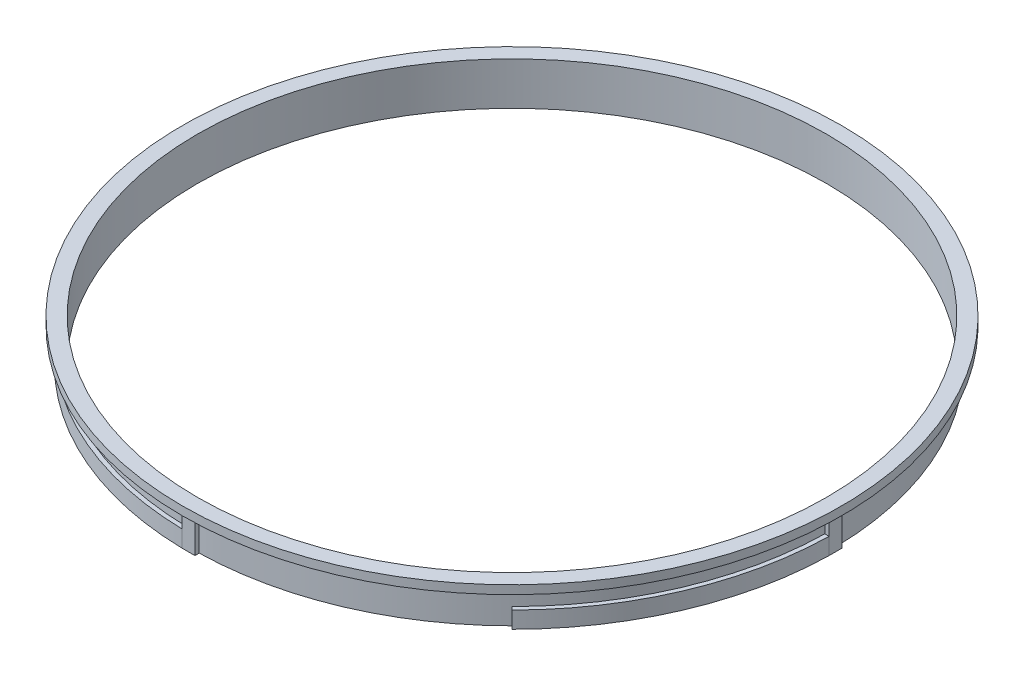
SolidWorks part; units mm, degrees
ref_plane "前视基准面" through (0, 0, 0) normal (0, 0, 1) x (1, 0, 0)
ref_plane "上视基准面" through (0, 0, 0) normal (0, 1, 0) x (1, 0, 0)
ref_plane "右视基准面" through (0, 0, 0) normal (1, 0, 0) x (0, 0, -1)
sketch "草图1" plane through (0, 0, 0) normal (0, 1, 0) x (1, 0, 0)
  circle A0 centre (0, 0) radius 73.5
  circle A1 centre (0, 0) radius 74.6
  dimension "D1" = 147
  dimension "D2" = 149.2
extrude "凸台-拉伸1" add sketch "草图1" along normal blind 10
sketch "草图2" plane through (0, 0, 0) normal (0, 1, 0) x (1, 0, 0)
  line L0 (0, 0) -> (74.6, 0) construction
  line L2 (75.5849, -1.5) -> (74.5849, -1.5)
  line L3 (75.5849, -1.5) -> (75.5849, 1.5)
  line L4 (75.5849, 1.5) -> (74.5849, 1.5)
  line L5 (74.5849, -1.5) -> (74.5849, 1.5)
  line L6 (75.5849, -1.5) -> (74.5849, 1.5) construction
  line L7 (75.5849, 1.5) -> (74.5849, -1.5) construction
  line L31 (-1.5, -75.5849) -> (-1.5, -74.5849)
  line L32 (-1.5, -75.5849) -> (1.5, -75.5849)
  line L33 (-1.5, -74.5849) -> (1.5, -74.5849)
  line L34 (1.5, -75.5849) -> (1.5, -74.5849)
  line L35 (-75.5849, 1.5) -> (-74.5849, 1.5)
  line L36 (-75.5849, 1.5) -> (-75.5849, -1.5)
  line L37 (-74.5849, 1.5) -> (-74.5849, -1.5)
  line L38 (-75.5849, -1.5) -> (-74.5849, -1.5)
  line L39 (1.5, 75.5849) -> (1.5, 74.5849)
  line L40 (1.5, 75.5849) -> (-1.5, 75.5849)
  line L41 (1.5, 74.5849) -> (-1.5, 74.5849)
  line L42 (-1.5, 75.5849) -> (-1.5, 74.5849)
  circle A0 centre (0, 0) radius 74.6 construction
  point P6 (75.0849, 0)
  point P11 (0, 0)
  point P24 (0, 0)
  point P27 (0, 0)
  dimension "D1" = 1
  dimension "D2" = 3
  dimension "D3" = 4
extrude "凸台-拉伸2" add sketch "草图2" along normal up to surface (10 mm away) up to face at (0, 10, 74.6)
sketch "草图3" plane through (0, 0, 0) normal (0, 1, 0) x (1, 0, 0)
  line L0 (0, 75.835) -> (0, 0) construction
  line L2 (0, 0) -> (53.4571, 53.4571) construction
  line L11 (1.5, 75.5849) -> (1.5, 74.5849)
  line L13 (53.4571, 53.4571) -> (52.7502, 52.7502)
  line L14 (53.4571, -53.4571) -> (52.7502, -52.7502)
  line L16 (75.5849, -1.5) -> (74.5849, -1.5)
  line L17 (-53.4571, -53.4571) -> (-52.7502, -52.7502)
  line L18 (-1.5, -75.5849) -> (-1.5, -74.5849)
  line L19 (-53.4571, 53.4571) -> (-52.7502, 52.7502)
  line L20 (-75.5849, 1.5) -> (-74.5849, 1.5)
  arc A0 (1.5, 75.5849) -> (53.4571, 53.4571) centre (0, 0) cw
  arc A1 (52.7502, 52.7502) -> (1.5, 74.5849) centre (0, 0) ccw
  arc A2 (52.7502, -52.7502) -> (74.5849, -1.5) centre (0, 0) ccw
  arc A11 (75.5849, -1.5) -> (53.4571, -53.4571) centre (0, 0) cw
  circle A12 centre (0, 0) radius 74.6 construction
  arc A14 (-52.7502, -52.7502) -> (-1.5, -74.5849) centre (0, 0) ccw
  arc A15 (-1.5, -75.5849) -> (-53.4571, -53.4571) centre (0, 0) cw
  arc A17 (-52.7502, 52.7502) -> (-74.5849, 1.5) centre (0, 0) ccw
  arc A18 (-75.5849, 1.5) -> (-53.4571, 53.4571) centre (0, 0) cw
  point P6 (0, 0)
  point P7 (0, 0)
  point P8 (0, 0)
  point P9 (0, 0)
  point P13 (0, 0)
  point P23 (0, 0)
  point P25 (0, 0)
  point P28 (0, 0)
  point P29 (1.35, 75.835)
  point P30 (1.35, 74.8378)
  point P32 (0, 0)
  point P33 (0, 0)
  point P34 (0, 0)
  point P36 (0, 0)
  point P37 (1.5, 75.835)
  dimension "D1" = 45
  dimension "D2" = 4
extrude "凸台-拉伸4" add sketch "草图3" along normal blind 3.9
sketch "草图4" plane through (0, 10, 0) normal (0, 1, 0) x (1, 0, 0)
  circle A0 centre (0, 0) radius 77
  circle A1 centre (0, 0) radius 74.6
  dimension "D1" = 154
extrude "凸台-拉伸5" add sketch "草图4" against normal blind 2
